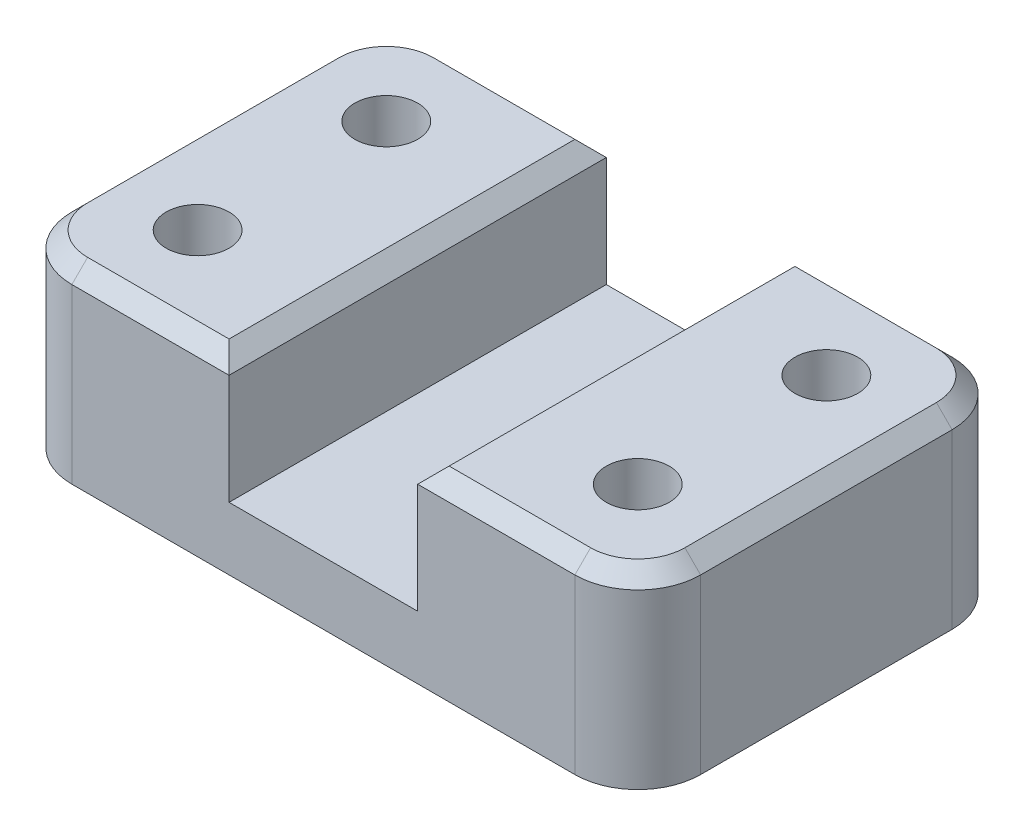
SolidWorks part; units mm, degrees
ref_plane "Front Plane" through (0, 0, 0) normal (0, 0, 1) x (1, 0, 0)
ref_plane "Top Plane" through (0, 0, 0) normal (0, 1, 0) x (1, 0, 0)
ref_plane "Right Plane" through (0, 0, 0) normal (1, 0, 0) x (0, 0, -1)
sketch "Sketch1" plane through (0, 0, 0) normal (0, 1, 0) x (1, 0, 0)
  line L0 (0, 986.5667) -> (0, 0) construction
  line L1 (-2500, -1500) -> (2500, -1500)
  line L2 (-2500, -1500) -> (-2500, 1500)
  line L3 (-2500, 1500) -> (2500, 1500)
  line L4 (2500, -1500) -> (2500, 1500)
  line L5 (-2500, -1500) -> (2500, 1500) construction
  line L6 (-2500, 1500) -> (2500, -1500) construction
  line L7 (0, 0) -> (-2082.644, 0) construction
  circle A0 centre (-1750, 750) radius 250
  circle A1 centre (1750, 750) radius 250
  circle A2 centre (1750, -750) radius 250
  circle A3 centre (-1750, -750) radius 250
  point P0 (0, 0)
  dimension "D3" = 500
  dimension "D1" = 5000
  dimension "D2" = 3000
  dimension "D4" = 750
  dimension "D5" = 750
extrude "Boss-Extrude1" add sketch "Sketch1" along normal blind 1500
sketch "Sketch2" plane through (0, 1500, 0) normal (0, 1, 0) x (1, 0, 0)
  line L0 (2500, 1500) -> (-2500, 1500) construction
  line L1 (750, -1500) -> (-750, -1500)
  line L2 (750, -1500) -> (750, 1500)
  line L3 (750, 1500) -> (-750, 1500)
  line L4 (-750, -1500) -> (-750, 1500)
  line L5 (750, -1500) -> (-750, 1500) construction
  line L6 (750, 1500) -> (-750, -1500) construction
  point P0 (0, 0)
  dimension "D1" = 1500
extrude "Cut-Extrude1" cut sketch "Sketch2" against normal blind 1000
fillet "Fillet1" radius 500 4 edges at (-2500, 750, -1500) (-2500, 750, 1500) (2500, 750, -1500) (2500, 750, 1500)
chamfer "Chamfer1" distance 125 angle 45 12 edges at (1375, 1500, -1500) (2353.5534, 1500, -1353.5534) (2500, 1500, 0) (2353.5534, 1500, 1353.5534) (750, 1500, 0) (1375, 1500, 1500) (-1375, 1500, -1500) (-2353.5534, 1500, -1353.5534) (-2500, 1500, 0) (-2353.5534, 1500, 1353.5534) (-750, 1500, 0) (-1375, 1500, 1500)
